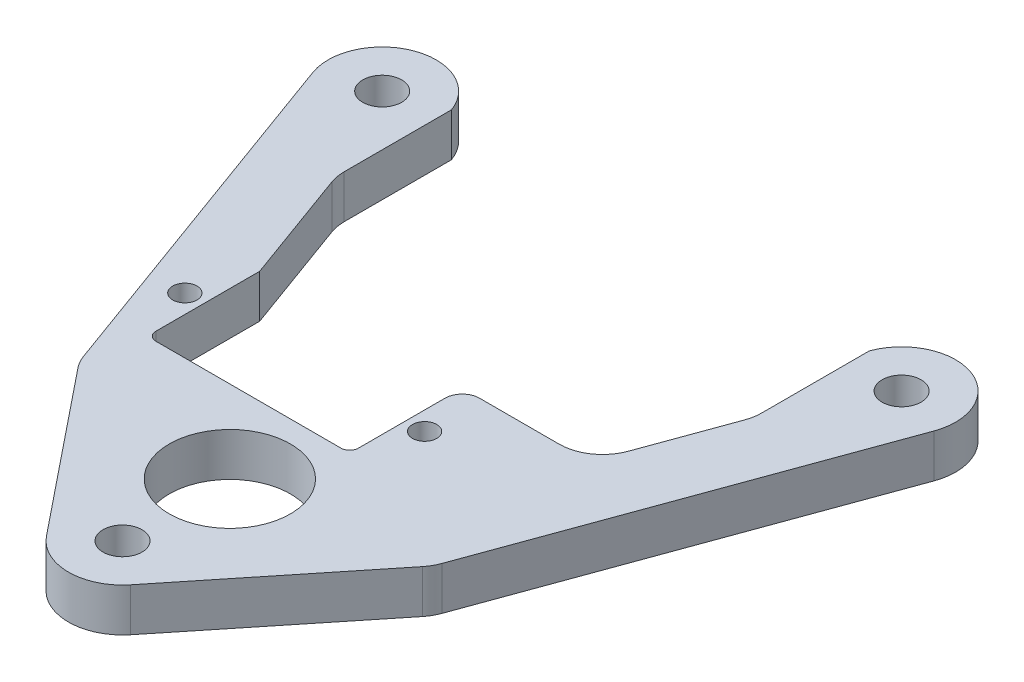
SolidWorks part; units mm, degrees
ref_plane "Front Plane" through (0, 0, 0) normal (0, 0, 1) x (1, 0, 0)
ref_plane "Top Plane" through (0, 0, 0) normal (0, 1, 0) x (1, 0, 0)
ref_plane "Right Plane" through (0, 0, 0) normal (1, 0, 0) x (0, 0, -1)
sketch "Sketch2" plane through (0, 0, 0) normal (0, 1, 0) x (1, 0, 0)
  line L0 (-21.2, 0) -> (6.5, 0) construction
  line L2 (4.35, -6.5) -> (-19.05, -6.5)
  line L3 (4.35, -6.5) -> (4.35, 6.5)
  line L4 (4.35, 6.5) -> (-19.05, 6.5)
  line L5 (-19.05, -6.5) -> (-19.05, 6.5)
  line L6 (4.35, -6.5) -> (-19.05, 6.5) construction
  line L7 (4.35, 6.5) -> (-19.05, -6.5) construction
  circle A0 centre (0, 0) radius 6.8505 construction
  circle A1 centre (6.5, 0) radius 1.4
  circle A2 centre (-21.2, 0) radius 1.4
  circle A3 centre (0, 0) radius 1.4 construction
  point P10 (-7.35, 0)
  dimension "D2" = 2.8
  dimension "D1" = 27.7
  dimension "D3" = 6.5
  dimension "D4" = 23.4
  dimension "D5" = 13
sketch "Sketch1" plane through (0, 0, 0) normal (0, 1, 0) x (1, 0, 0)
  line L0 (0, 0) -> (30, 0) construction
  line L1 (30, 0) -> (30, 31.6) construction
  line L2 (0, 9) -> (15.1232, 9)
  line L3 (15.1232, 9) -> (24.1269, 33.7376)
  line L5 (20.418, -13) -> (35.8731, 29.4624)
  line L6 (0, 9) -> (0, -9)
  line L7 (4.35, 6.5) -> (-19.05, 6.5) construction
  line L8 (30, 31.6) -> (0, 31.6) construction
  line L9 (20.418, -13) -> (4.8688, -32.3188)
  line L10 (0, -28.4) -> (0, 0) construction
  line L11 (0, -28.4) -> (0, -34.65) construction
  line L12 (0, -26.15) -> (0, -9)
  line L13 (0, -30.65) -> (0, -34.65)
  circle A0 centre (30, 31.6) radius 2.25
  arc A1 (35.8731, 29.4624) -> (24.1269, 33.7376) centre (30, 31.6) ccw
  arc A2 (0, -30.65) -> (0, -26.15) centre (0, -28.4) ccw
  arc A3 (0, -34.65) -> (4.8688, -32.3188) centre (0, -28.4) ccw
  point P5 (16.0713, -5.1237)
  point P15 (0, 0)
  point P18 (27.4919, 0)
  point P22 (23.5359, -9)
  point P23 (22.8637, -12.6807)
  dimension "D3" = 4
  dimension "D4" = 4.5
  dimension "D1" = 31.6
  dimension "D2" = 30
  dimension "D5" = 2.5
  dimension "D6" = 110
  dimension "D7" = 28.4
  dimension "D8" = 13
extrude "Boss-Extrude1" add sketch "Sketch1" along normal blind 5
mirror "Mirror1" about plane through (0, 0, 0) normal (1, 0, 0) of "Boss-Extrude1"
sketch "Sketch3" plane through (0, 5, 0) normal (0, 1, 0) x (1, 0, 0)
  line L0 (-24.1269, 33.7376) -> (-24.1269, 20.4487)
  line L1 (-24.1269, 20.4487) -> (-19.05, 6.5)
  line L2 (-19.05, 6.5) -> (0, 6.5)
  line L3 (4.35, 6.5) -> (-19.05, 6.5) construction
  line L4 (0, 6.5) -> (0, 9)
  line L9 (15.1232, 9) -> (-15.1232, 9)
  line L10 (-15.1232, 9) -> (-24.1269, 33.7376)
  line L12 (-15.1232, 9) -> (-24.1269, 33.7376)
  line L14 (4.8688, -32.3188) -> (20.418, -13)
  line L16 (20.418, -13) -> (35.8731, 29.4624)
  line L17 (24.1269, 33.7376) -> (15.1232, 9)
  line L18 (15.1232, 9) -> (-15.1232, 9)
  line L23 (4.8688, -32.3188) -> (20.418, -13)
  line L25 (20.418, -13) -> (35.8731, 29.4624)
  line L26 (24.1269, 33.7376) -> (15.1232, 9)
  line L32 (-35.8731, 29.4624) -> (-20.418, -13)
  line L33 (-35.8731, 29.4624) -> (-20.418, -13)
  line L36 (-20.418, -13) -> (-4.8688, -32.3188)
  line L37 (-20.418, -13) -> (-4.8688, -32.3188)
  arc A3 (-24.1269, 33.7376) -> (-35.8731, 29.4624) centre (-30, 31.6) ccw
  arc A4 (-4.8688, -32.3188) -> (4.8688, -32.3188) centre (0, -28.4) ccw
  arc A5 (35.8731, 29.4624) -> (24.1269, 33.7376) centre (30, 31.6) ccw
  arc A7 (-4.8688, -32.3188) -> (4.8688, -32.3188) centre (0, -28.4) ccw
  arc A8 (35.8731, 29.4624) -> (24.1269, 33.7376) centre (30, 31.6) ccw
  arc A10 (-24.1269, 33.7376) -> (-35.8731, 29.4624) centre (-30, 31.6) ccw
  line M14 (15.1232, 9) -> (-15.1232, 9)
  line M15 (-15.1232, 9) -> (-24.1269, 33.7376)
  dimension "D1" = 0
extrude "Cut-Extrude1" cut sketch "Sketch3" against normal through all both and the other way through all contours L2 L4 L0 L1 M14 M15
mirror "Mirror2" about plane through (0, 0, 0) normal (1, 0, 0) of "Cut-Extrude1"
sketch "Sketch4" plane through (0, 5, 0) normal (0, 1, 0) x (1, 0, 0)
  line L0 (4.35, -6.5) -> (4.35, 6.5) construction
  line L1 (4.35, -6.5) -> (-19.05, -6.5) construction
  line L2 (-19.05, -6.5) -> (-19.05, 6.5) construction
  line L3 (4.35, -6.5) -> (4.35, 6.5)
  line L4 (4.35, -6.5) -> (-19.05, -6.5)
  line L5 (-19.05, -6.5) -> (-19.05, 6.5)
  line L6 (-19.05, 6.5) -> (4.35, 6.5)
  circle A0 centre (6.5, 0) radius 1.4 construction
  circle A1 centre (-21.2, 0) radius 1.4 construction
  circle A2 centre (6.5, 0) radius 1.4
  circle A3 centre (-21.2, 0) radius 1.4
extrude "Cut-Extrude2" cut sketch "Sketch4" against normal through all both and the other way through all
fillet "Fillet1" radius 5 5 edges at (20.418, 2.5, 13) (-20.418, 2.5, 13) (24.1269, 2.5, -20.4487) (19.05, 2.5, -6.5) (-24.1269, 2.5, -20.4487)
fillet "Fillet2" radius 1 2 edges at (4.35, 2.5, 6.5) (-19.05, 2.5, 6.5)
fillet "Fillet3" radius 2 1 edges at (4.35, 2.5, -6.5)
ref_plane "Plane1" through (-7.35, 0, 0) normal (1, 0, 0) x (0, 0, -1)
sketch "Sketch5" plane through (0, 5, 0) normal (0, 1, 0) x (1, 0, 0)
  line L0 (0, -2.75) -> (0, 2.75) construction
  circle A0 centre (0, -16) radius 7
  point P4 (0, -15.9979)
  dimension "D1" = 14
  dimension "D2" = 16
extrude "Cut-Extrude3" cut sketch "Sketch5" against normal through all
